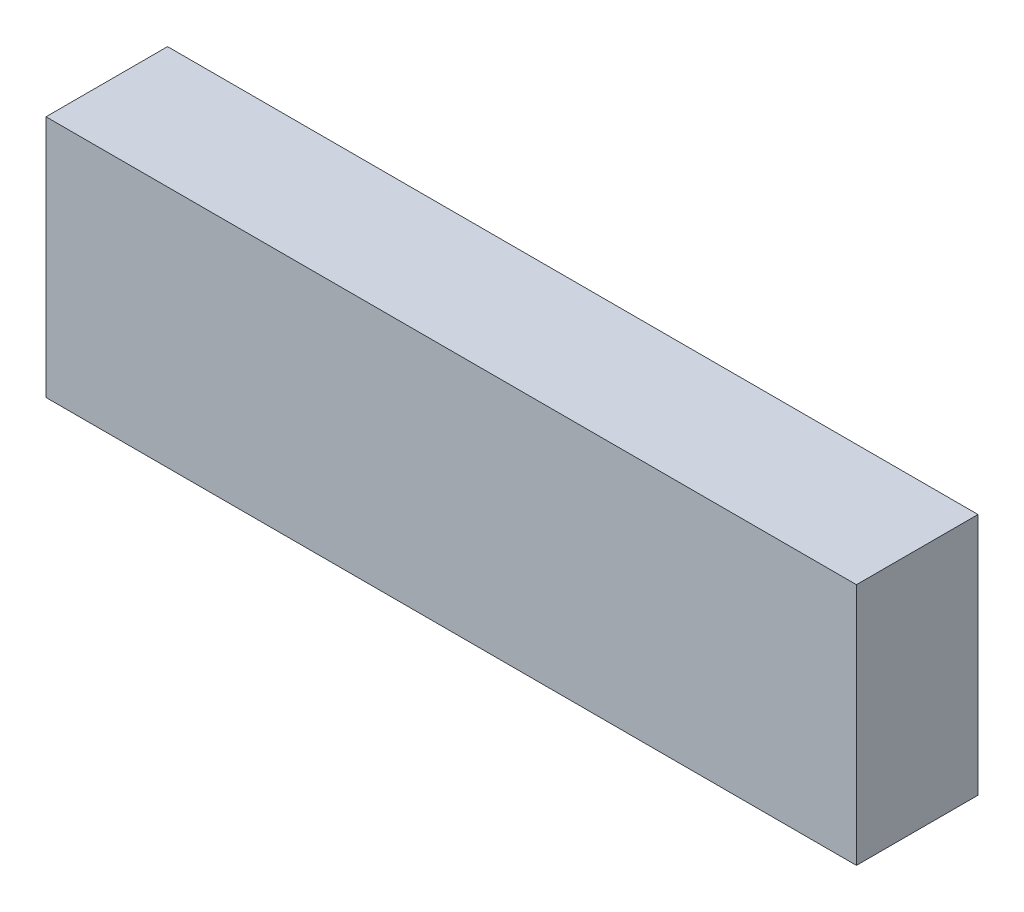
SolidWorks part; units mm, degrees
material "1060 Alloy"
ref_plane "Front Plane" through (0, 0, 0) normal (0, 0, 1) x (1, 0, 0)
ref_plane "Top Plane" through (0, 0, 0) normal (0, 1, 0) x (1, 0, 0)
ref_plane "Right Plane" through (0, 0, 0) normal (1, 0, 0) x (0, 0, -1)
sketch "Sketch1" plane through (0, 0, 0) normal (0, 0, 1) x (1, 0, 0)
  line L1 (0, 0) -> (1000, 0)
  line L2 (0, 0) -> (0, 300)
  line L3 (0, 300) -> (1000, 300)
  line L4 (1000, 0) -> (1000, 300)
  dimension "Length" = 1000
  dimension "Width" = 300
extrude "Boss-Extrude1" add sketch "Sketch1" along normal blind 150
